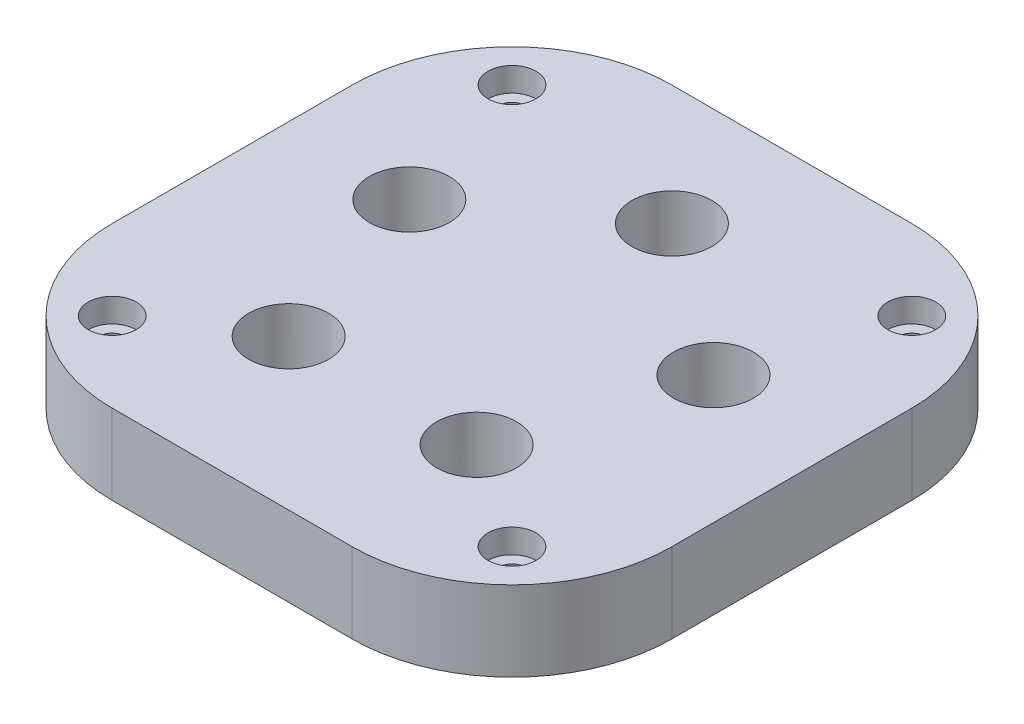
SolidWorks part; units mm, degrees
ref_plane "前视基准面" through (0, 0, 0) normal (0, 0, 1) x (1, 0, 0)
ref_plane "上视基准面" through (0, 0, 0) normal (0, 1, 0) x (1, 0, 0)
ref_plane "右视基准面" through (0, 0, 0) normal (1, 0, 0) x (0, 0, -1)
sketch "草图1" plane through (0, 0, 0) normal (0, 1, 0) x (1, 0, 0)
  line L1 (20, 0) -> (50, 0)
  line L2 (0, 20) -> (0, 50)
  line L3 (20, 70) -> (50, 70)
  line L4 (70, 20) -> (70, 50)
  arc A1 (20, 0) -> (0, 20) centre (20, 20) cw
  arc A2 (50, 0) -> (70, 20) centre (50, 20) ccw
  arc A3 (50, 70) -> (70, 50) centre (50, 50) cw
  arc A4 (0, 50) -> (20, 70) centre (20, 50) cw
  circle A5 centre (10, 60) radius 1.6
  circle A6 centre (60, 60) radius 1.6
  circle A7 centre (60, 10) radius 1.6
  circle A8 centre (10, 10) radius 1.6
  point P8 (0, 0)
  point P11 (70, 0)
  point P16 (0, 70)
  dimension "D1" = 70
  dimension "D3" = 20
  dimension "D6" = 3.2
  dimension "D2" = 70
  dimension "D4" = 10
  dimension "D5" = 10
  dimension "D7" = 10
  dimension "D8" = 10
extrude "凸台-拉伸1" add sketch "草图1" along normal blind 10
sketch "草图2" plane through (0, 10, 0) normal (0, 1, 0) x (1, 0, 0)
  line L0 (50, 70) -> (20, 70) construction
  line L1 (0, 50) -> (0, 20) construction
  circle A0 centre (35, 55) radius 5
  circle A1 centre (54.0211, 41.1803) radius 5
  circle A2 centre (46.7557, 18.8197) radius 5
  circle A3 centre (23.2443, 18.8197) radius 5
  circle A4 centre (15.9789, 41.1803) radius 5
  point P2 (35, 35)
  point P5 (35, 70)
  point P8 (0, 35)
  point P20 (35, 35)
  dimension "D2" = 10
  dimension "D1" = 20
  dimension "D3" = 5
extrude "切除-拉伸1" cut sketch "草图2" against normal blind 25
sketch "草图3" plane through (0, 10, 0) normal (0, 1, 0) x (1, 0, 0)
  circle A0 centre (10, 60) radius 3
  circle A1 centre (60, 60) radius 3
  circle A2 centre (60, 10) radius 3
  circle A3 centre (10, 10) radius 3
  dimension "D1" = 6
  dimension "D2" = 6
extrude "切除-拉伸2" cut sketch "草图3" against normal blind 3
sketch "草图4" plane through (0, 0, 0) normal (0, -1, 0) x (1, 0, 0)
  line L0 (0, -50) -> (0, -20) construction
  line L1 (20, 0) -> (50, 0) construction
  circle A1 centre (15.9789, -41.1803) radius 5 construction
  circle A2 centre (35, -55) radius 5 construction
  circle A3 centre (54.0211, -41.1803) radius 5 construction
  circle A4 centre (46.7557, -18.8197) radius 5 construction
  circle A5 centre (23.2443, -18.8197) radius 5 construction
  circle A6 centre (15.9789, -41.1803) radius 5
  circle A7 centre (35, -55) radius 5
  circle A8 centre (54.0211, -41.1803) radius 5
  circle A9 centre (46.7557, -18.8197) radius 5
  circle A10 centre (23.2443, -18.8197) radius 5
  circle A11 centre (35, -35) radius 3.5
  dimension "D4" = 7
  dimension "D1" = 35
  dimension "D2" = 35
extrude "切除-拉伸3" cut sketch "草图4" against normal blind 5
